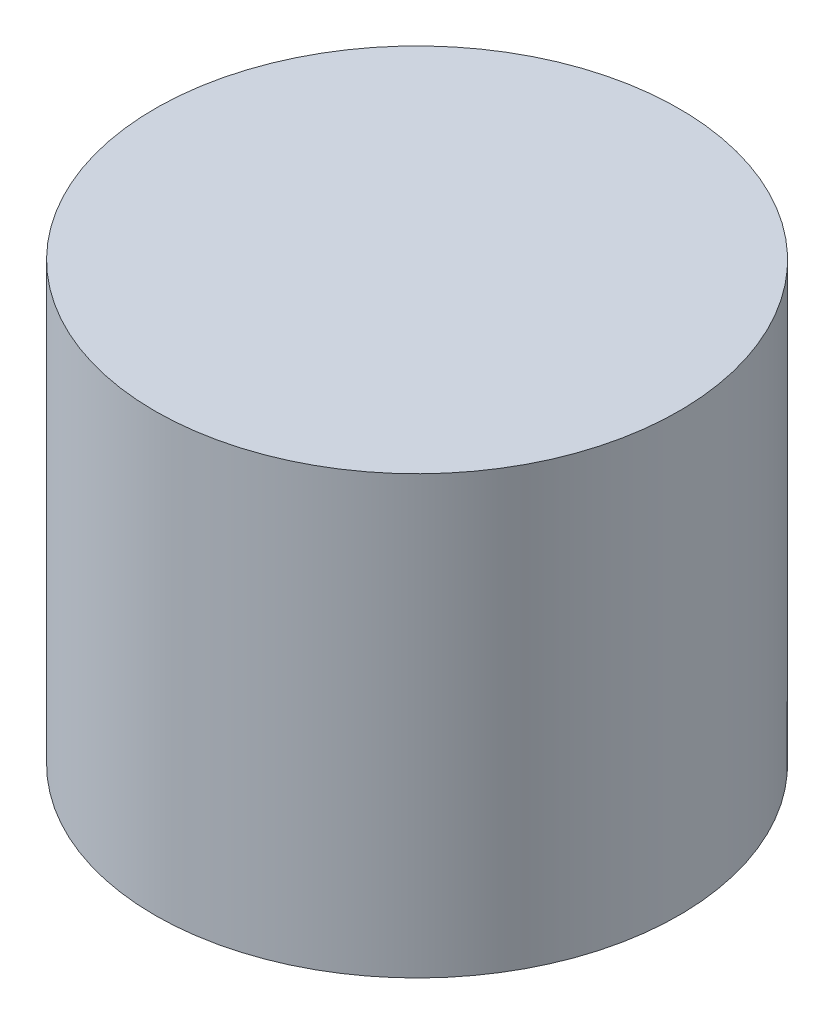
SolidWorks part; units mm, degrees
ref_plane "Front Plane" through (0, 0, 0) normal (0, 0, 1) x (1, 0, 0)
ref_plane "Top Plane" through (0, 0, 0) normal (0, 1, 0) x (1, 0, 0)
ref_plane "Right Plane" through (0, 0, 0) normal (1, 0, 0) x (0, 0, -1)
sketch "Sketch1" plane through (0, 0, 0) normal (0, 1, 0) x (1, 0, 0)
  circle A0 centre (0, 0) radius 30
extrude "Boss-Extrude1" add sketch "Sketch1" along normal blind 50
